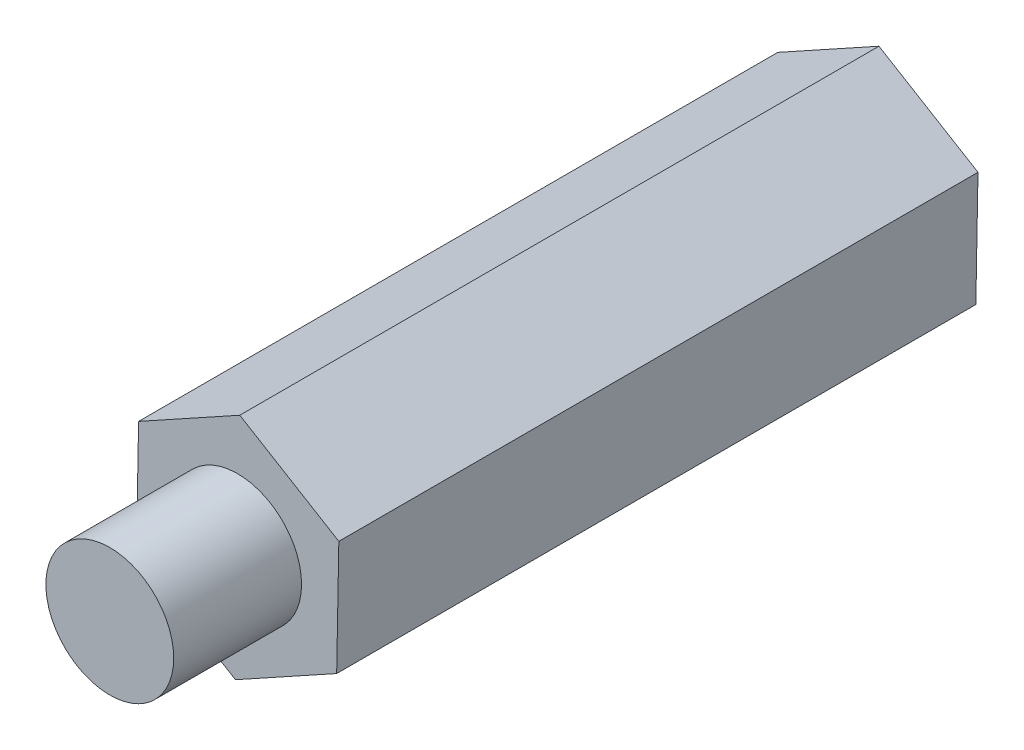
SolidWorks part; units mm, degrees
ref_plane "前视基准面" through (0, 0, 0) normal (0, 0, 1) x (1, 0, 0)
ref_plane "上视基准面" through (0, 0, 0) normal (0, 1, 0) x (1, 0, 0)
ref_plane "右视基准面" through (0, 0, 0) normal (1, 0, 0) x (0, 0, -1)
other "Configuration Table"
sketch "草图1" plane through (0, 0, 0) normal (0, 0, 1) x (1, 0, 0)
  line L1 (-2.3242, 1.4005) -> (-2.375, -1.3126)
  line L2 (-2.375, -1.3126) -> (-0.0508, -2.7131)
  line L3 (-0.0508, -2.7131) -> (2.3242, -1.4005)
  line L4 (2.3242, -1.4005) -> (2.375, 1.3126)
  line L5 (2.375, 1.3126) -> (0.0508, 2.7131)
  line L6 (0.0508, 2.7131) -> (-2.3242, 1.4005)
  circle A0 centre (0, 0) radius 2.35 construction
  point P1 (-1.1367, 2.0568)
  point P10 (1.1367, -2.0568)
  dimension "D1" = 4.7
extrude "凸台-拉伸1" add sketch "草图1" along normal blind 15
sketch "草图2" plane through (0, 0, 15) normal (0, 0, 1) x (1, 0, 0)
  circle A0 centre (0, 0) radius 1.5
  dimension "D1" = 3
extrude "凸台-拉伸2" add sketch "草图2" along normal blind 3
sketch "草图3" plane through (0, 0, 0) normal (0, 0, -1) x (-1, 0, 0)
  circle A0 centre (0, 0) radius 1.5
  dimension "D1" = 3
extrude "切除-拉伸1" cut sketch "草图3" against normal blind 3
